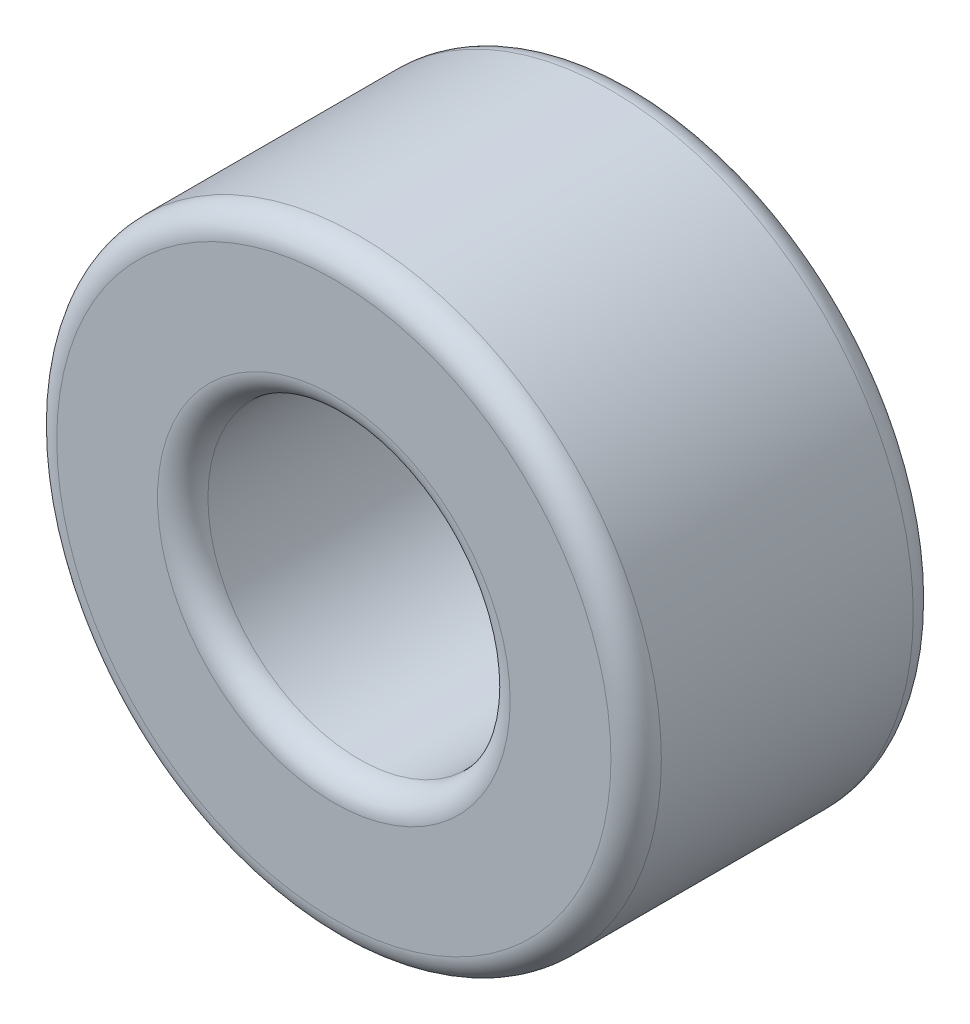
SolidWorks part; units mm, degrees
ref_plane "前视基准面" through (0, 0, 0) normal (0, 0, 1) x (1, 0, 0)
ref_plane "上视基准面" through (0, 0, 0) normal (0, 1, 0) x (1, 0, 0)
ref_plane "右视基准面" through (0, 0, 0) normal (1, 0, 0) x (0, 0, -1)
other "Configuration Table"
sketch "草图1" plane through (0, 0, 0) normal (0, 0, 1) x (1, 0, 0)
  circle A0 centre (0, 0) radius 3
  circle A1 centre (0, 0) radius 6
  dimension "D1" = 6
  dimension "D2" = 12
extrude "凸台-拉伸1" add sketch "草图1" along normal blind 6
fillet "圆角1" radius 0.5 4 edges at (6, 0, 0) (3, 0, 0) (3, 0, 6) (6, 0, 6)
